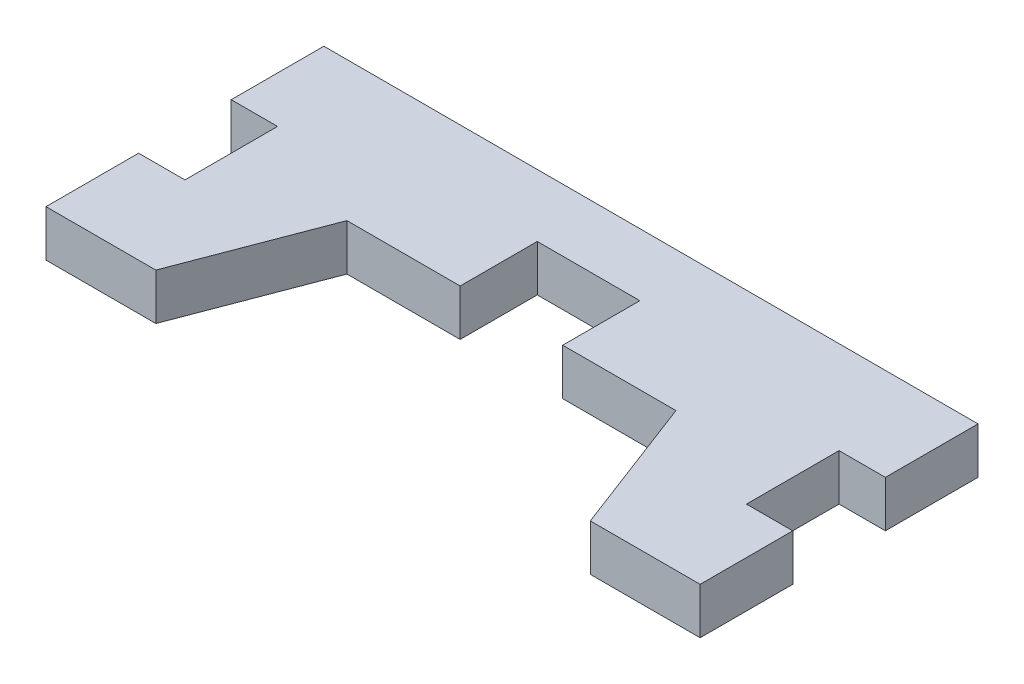
SolidWorks part; units mm, degrees
ref_plane "Front Plane" through (0, 0, 0) normal (0, 0, 1) x (1, 0, 0)
ref_plane "Top Plane" through (0, 0, 0) normal (0, 1, 0) x (1, 0, 0)
ref_plane "Right Plane" through (0, 0, 0) normal (1, 0, 0) x (0, 0, -1)
sketch "Sketch1" plane through (0, 0, 0) normal (0, 1, 0) x (1, 0, 0)
  line L0 (18.7086, -16.8038) -> (4.4782, -16.8038)
  line L1 (4.4782, -16.8038) -> (4.4782, -4.8038)
  line L2 (4.4782, -4.8038) -> (10.4782, -4.8038)
  line L3 (10.4782, -4.8038) -> (10.4782, 7.1962)
  line L4 (10.4782, 7.1962) -> (4.4782, 7.1962)
  line L5 (4.4782, 7.1962) -> (4.4782, 19.1962)
  line L6 (4.4782, 19.1962) -> (89.2254, 19.1962)
  line L7 (89.2254, 19.1962) -> (89.2254, 7.1962)
  line L8 (89.2254, 7.1962) -> (83.2254, 7.1962)
  line L9 (83.2254, 7.1962) -> (83.2254, -4.8038)
  line L10 (83.2254, -4.8038) -> (89.2254, -4.8038)
  line L11 (89.2254, -4.8038) -> (89.2254, -16.8038)
  line L12 (89.2254, -16.8038) -> (74.995, -16.8038)
  line L13 (74.995, -16.8038) -> (68.1647, 1.123)
  line L14 (68.1647, 1.123) -> (53.4968, 1.123)
  line L15 (25.5389, 1.123) -> (18.7086, -16.8038)
  line L16 (4.4782, 16.1941) -> (89.2254, 16.1941) construction
  line L18 (40.2069, 1.123) -> (25.5389, 1.123)
  line L20 (40.2069, 1.123) -> (40.2069, 11.1136)
  line L21 (40.2069, 11.1136) -> (53.4968, 11.1136)
  line L22 (53.4968, 1.123) -> (53.4968, 11.1136)
  point P17 (46.8518, 19.1962)
  point P25 (46.8518, 11.1136)
extrude "Boss-Extrude1" add sketch "Sketch1" along normal blind 6
